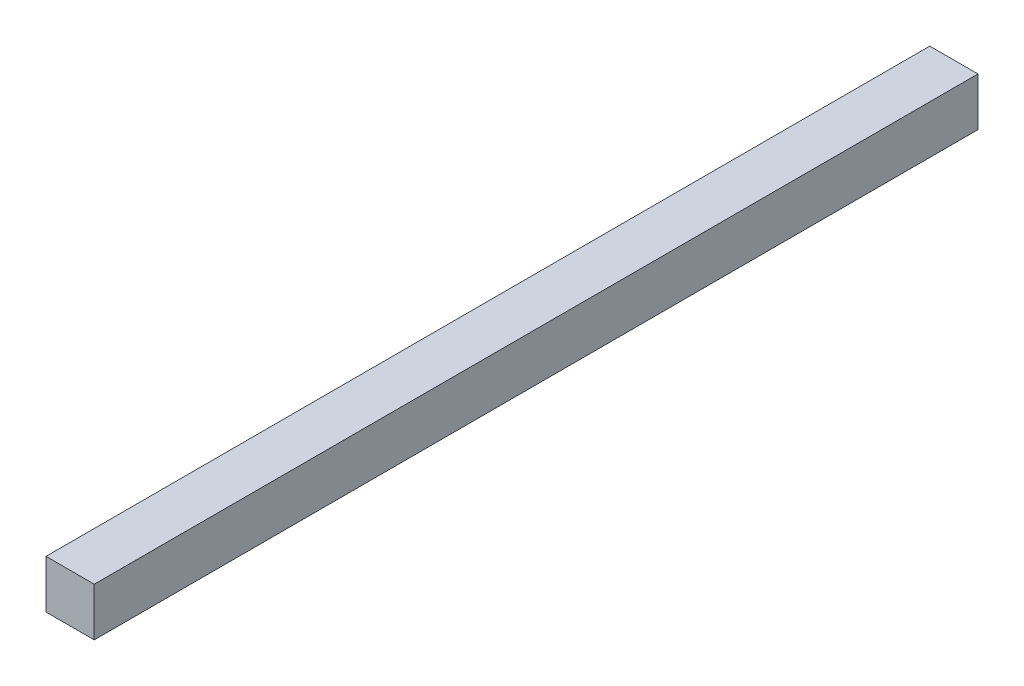
SolidWorks part; units mm, degrees
ref_plane "Alzado" through (0, 0, 0) normal (0, 0, 1) x (1, 0, 0)
ref_plane "Planta" through (0, 0, 0) normal (0, 1, 0) x (1, 0, 0)
ref_plane "Vista lateral" through (0, 0, 0) normal (1, 0, 0) x (0, 0, -1)
sketch "Croquis1" plane through (0, 0, 0) normal (0, 0, 1) x (1, 0, 0)
  line L1 (6.35, -6.35) -> (-6.35, -6.35)
  line L2 (6.35, -6.35) -> (6.35, 6.35)
  line L3 (6.35, 6.35) -> (-6.35, 6.35)
  line L4 (-6.35, -6.35) -> (-6.35, 6.35)
  line L5 (6.35, -6.35) -> (-6.35, 6.35) construction
  line L6 (6.35, 6.35) -> (-6.35, -6.35) construction
  point P0 (0, 0)
  dimension "D1" = 12.7
  dimension "D2" = 12.7
extrude "Saliente-Extruir1" add sketch "Croquis1" along normal mid plane 232.7
